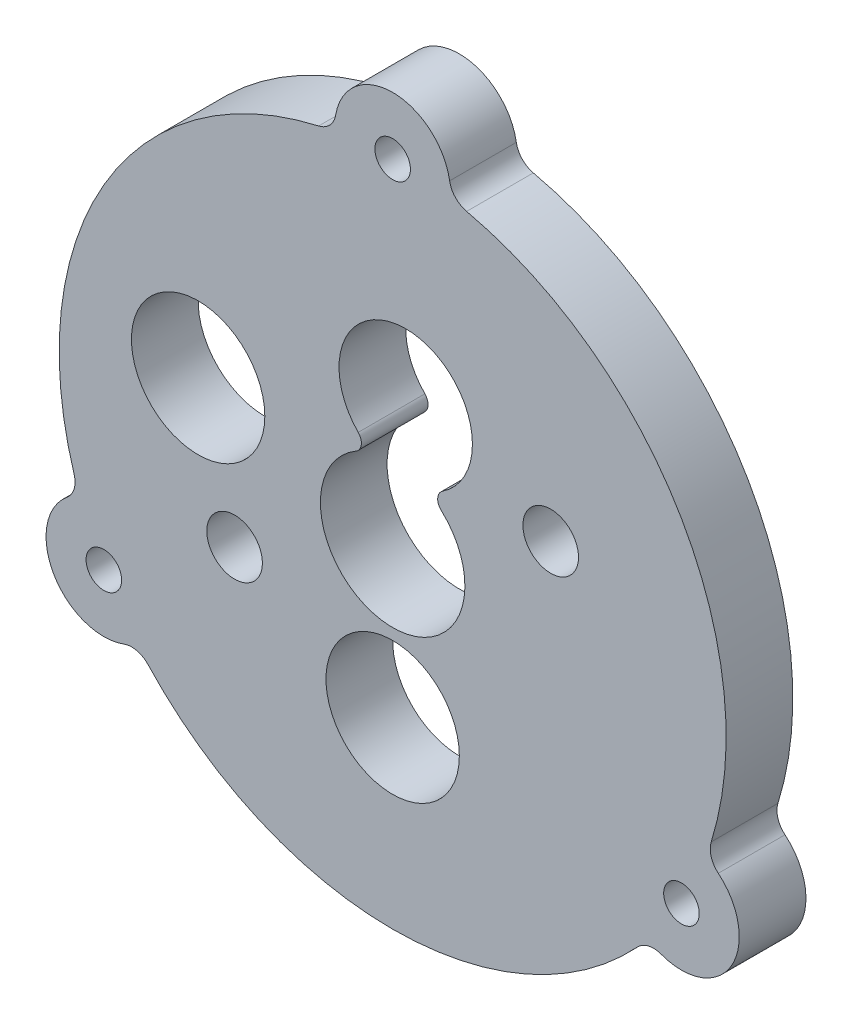
SolidWorks part; units mm, degrees
ref_plane "正面" through (0, 0, 0) normal (0, 0, 1) x (1, 0, 0)
ref_plane "平面" through (0, 0, 0) normal (0, 1, 0) x (1, 0, 0)
ref_plane "右側面" through (0, 0, 0) normal (1, 0, 0) x (0, 0, -1)
sketch "ｽｹｯﾁ1" plane through (0, 0, 0) normal (0, 0, 1) x (1, 0, 0)
  line L0 (0, 0) -> (0, -6.75) construction
  line L1 (0, -6.75) -> (-8.75, 2.1067) construction
  line L2 (-8.75, 2.1067) -> (0.5875, 5.6861) construction
  line L3 (0.5875, 5.6861) -> (0, -6.75) construction
  line L4 (-8.75, 2.1067) -> (0, 0) construction
  line L5 (-12.9904, -7.5) -> (0, 0) construction
  line L6 (7.1092, 3.6686) -> (-7.1092, -3.6686) construction
  circle A1 centre (-8.75, 2.1067) radius 3
  arc A2 (1.5633, 2.8493) -> (-0.9478, 3.1087) centre (0.5875, 5.6861) ccw
  circle A4 centre (0, -6.75) radius 3
  circle A5 centre (0, 15) radius 0.8
  circle A6 centre (12.9904, -7.5) radius 0.8
  circle A7 centre (-12.9904, -7.5) radius 0.8
  circle A8 centre (0, 0) radius 17.6 construction
  circle A9 centre (0, 0) radius 15 construction
  circle A10 centre (0, 15) radius 3 construction
  circle A11 centre (12.9904, -7.5) radius 3 construction
  circle A12 centre (-12.9904, -7.5) radius 3 construction
  arc A13 (-0.9478, 3.1087) -> (1.5633, 2.8493) centre (0, 0) ccw
  circle A14 centre (-7.1092, -3.6686) radius 1.25
  circle A15 centre (7.1092, 3.6686) radius 1.25
  arc A16 (-11.5001, -9.6305) -> (-14.0903, -5.1441) centre (-12.9904, -7.5) cw
  arc A17 (-2.5902, 14.7747) -> (2.5902, 14.7747) centre (0, 15) cw
  arc A18 (14.0903, -5.1441) -> (11.5001, -9.6305) centre (12.9904, -7.5) cw
  arc A19 (-2.5902, 14.7747) -> (-14.0903, -5.1441) centre (0, 0) ccw
  arc A20 (14.0903, -5.1441) -> (2.5902, 14.7747) centre (0, 0) ccw
  arc A21 (-11.5001, -9.6305) -> (11.5001, -9.6305) centre (0, 0) ccw
  point P20 (0, 0)
  point P24 (0, 0)
  point P26 (0, 0)
  point P30 (11.5001, -9.6305)
  point P31 (11.5001, -9.6305)
  point P38 (0, 0)
  point P43 (0, 0)
  dimension "D6" = 6
  dimension "D7" = 6.5
  dimension "D8" = 1.6
  dimension "D11" = 2.6
  dimension "D12" = 6
  dimension "D15" = 2.5
  dimension "D18" = 2.6
  dimension "D1" = 6.75
  dimension "D2" = 12.45
  dimension "D3" = 12.45
  dimension "D4" = 10
  dimension "D5" = 9
  dimension "D9" = 15
  dimension "D14" = 60
  dimension "D16" = 16
  dimension "D17" = 60
  dimension "D10" = 3
  dimension "D13" = 3
  dimension "D19" = 3
  dimension "D20" = 3
extrude "ﾎﾞｽ - 押し出し1" add sketch "ｽｹｯﾁ1" along normal blind 3
fillet "ﾌｨﾚｯﾄ1" radius 0.5 2 edges at (-0.9478, 3.1087, 1.5) (1.5633, 2.8493, 1.5)
fillet "ﾌｨﾚｯﾄ2" radius 1 6 edges at (-11.5001, -9.6305, 1.5) (-14.0903, -5.1441, 1.5) (2.5902, 14.7747, 1.5) (14.0903, -5.1441, 1.5) (11.5001, -9.6305, 1.5) (-2.5902, 14.7747, 1.5)
